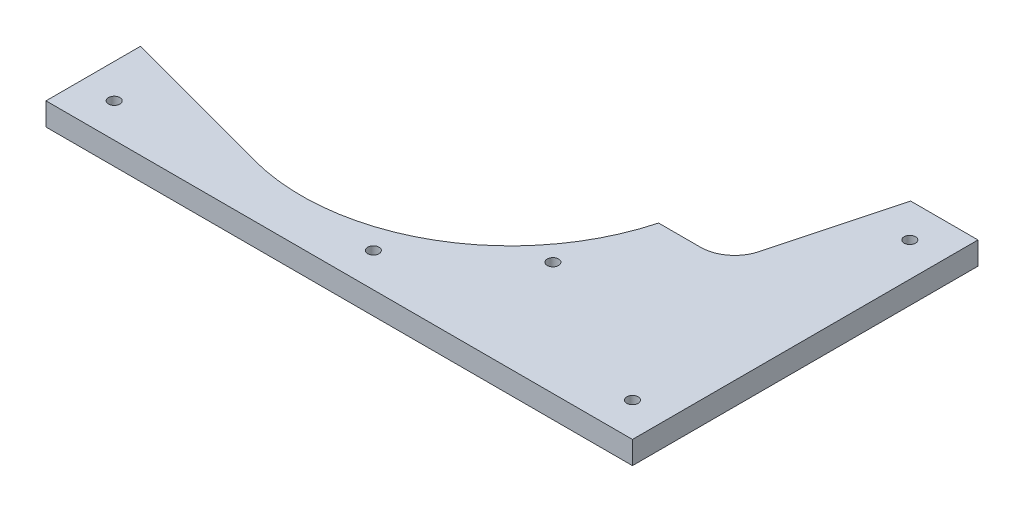
SolidWorks part; units mm, degrees
ref_plane "Front Plane" through (0, 0, 0) normal (0, 0, 1) x (1, 0, 0)
ref_plane "Top Plane" through (0, 0, 0) normal (0, 1, 0) x (1, 0, 0)
ref_plane "Right Plane" through (0, 0, 0) normal (1, 0, 0) x (0, 0, -1)
sketch "Sketch1" plane through (0, 0, 0) normal (0, 1, 0) x (1, 0, 0)
  line L0 (0, 116.84) -> (159.4744, 74.109) construction
  line L5 (0, 116.84) -> (159.4744, 116.84) construction
  line L6 (159.4744, 116.84) -> (159.4744, 74.109) construction
  line L7 (210.2744, -25.4) -> (210.2744, 167.64)
  line L8 (-30.2404, 3.9812) -> (-117.3856, 27.3317)
  line L12 (0, 0) -> (0, -25.4) construction
  line L13 (0, -25.4) -> (210.2744, -25.4)
  line L14 (0, -25.4) -> (-117.3856, -25.4)
  line L15 (-117.3856, -25.4) -> (-117.3856, 27.3317)
  line L17 (172.6735, 167.64) -> (210.2744, 167.64)
  line L18 (112.8588, 86.5996) -> (150.9588, 86.5996)
  line L19 (150.9588, 86.5996) -> (172.6735, 167.64)
  circle A0 centre (159.4744, 74.109) radius 50.8 construction
  circle A1 centre (159.4744, 74.109) radius 48.26 construction
  circle A2 centre (0, 116.84) radius 50.8 construction
  circle A3 centre (0, 116.84) radius 48.26 construction
  arc A4 (0, 0) -> (112.8588, 86.5996) centre (0, 116.84) ccw
  arc A5 (0, 0) -> (-30.2404, 3.9812) centre (0, 116.84) cw
  circle A6 centre (-98.3356, -6.35) radius 3.175
  circle A7 centre (46.4444, -6.35) radius 3.175
  circle A8 centre (102.3244, 38.1) radius 3.175
  circle A9 centre (191.2244, 148.59) radius 3.175
  circle A10 centre (191.2244, -6.35) radius 3.175
  dimension "D1" = 101.6
  dimension "D2" = 2.54
  dimension "D3" = 101.6
  dimension "D4" = 2.54
  dimension "D5" = 165.1
  dimension "D8" = 15
  dimension "D14" = 19.05
  dimension "D15" = 19.05
  dimension "D16" = 19.05
  dimension "D17" = 163.83
  dimension "D18" = 107.95
  dimension "D19" = 63.5
  dimension "D20" = 19.05
  dimension "D21" = 19.05
  dimension "D22" = 6.35
  dimension "D23" = 19.05
  dimension "D24" = 19.05
  dimension "D6" = 75
  dimension "D7" = 116.84
  dimension "D9" = 25.4
  dimension "D10" = 327.66
  dimension "D11" = 75
  dimension "D12" = 193.04
  dimension "D13" = 38.1
extrude "Boss-Extrude1" add sketch "Sketch1" along normal blind 12.7 contours A4 A5 L8 L15 L14 L13 L7 L17 L19 L18 A10 A9 A8 A7 A6
fillet "Fillet1" radius 19.05 1 edges at (150.9588, 6.35, -86.5996)
